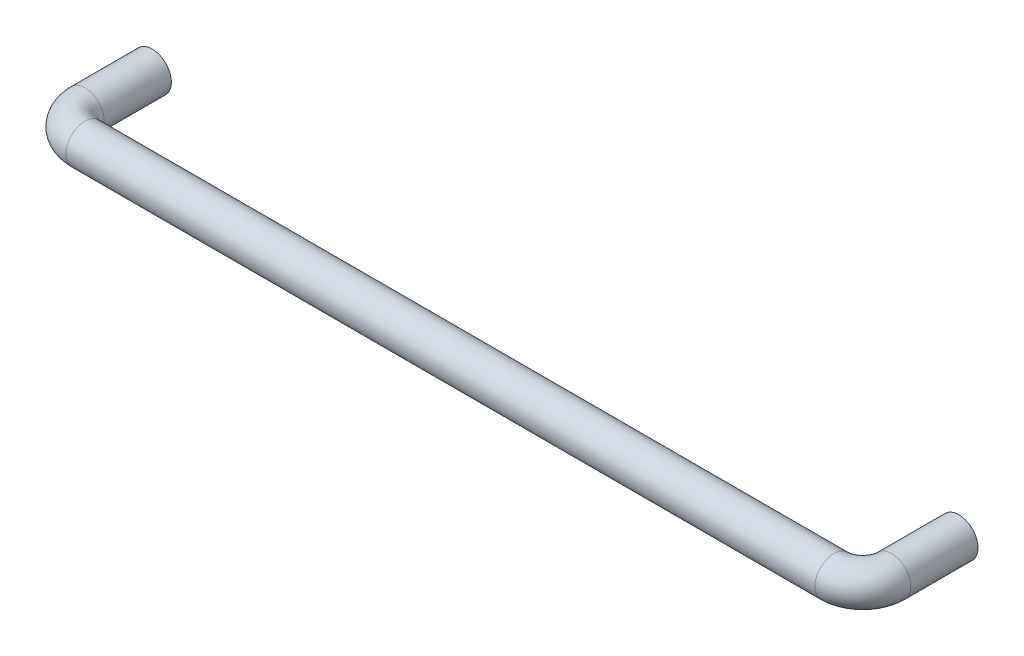
SolidWorks part; units mm, degrees
ref_plane "Front Plane" through (0, 0, 0) normal (0, 0, 1) x (1, 0, 0)
ref_plane "Top Plane" through (0, 0, 0) normal (0, 1, 0) x (1, 0, 0)
ref_plane "Right Plane" through (0, 0, 0) normal (1, 0, 0) x (0, 0, -1)
sketch "Sketch1" plane through (0, 0, 0) normal (0, 1, 0) x (1, 0, 0)
  line L0 (0, 0) -> (0, -3.5)
  line L1 (-1.5, -5) -> (-40.5, -5)
  line L2 (-42, -3.5) -> (-42, 0)
  arc A0 (-1.5, -5) -> (0, -3.5) centre (-1.5, -3.5) ccw
  arc A1 (-42, -3.5) -> (-40.5, -5) centre (-40.5, -3.5) ccw
  dimension "D1" = 3
  dimension "D5" = 3
  dimension "D2" = 3.5
  dimension "D3" = 42
sketch "Sketch2" plane through (0, 0, 0) normal (0, 0, 1) x (1, 0, 0)
  circle A0 centre (0, 0) radius 1
  dimension "D1" = 2
sweep "Sweep1" add profiles "Sketch2" path "Sketch1"
